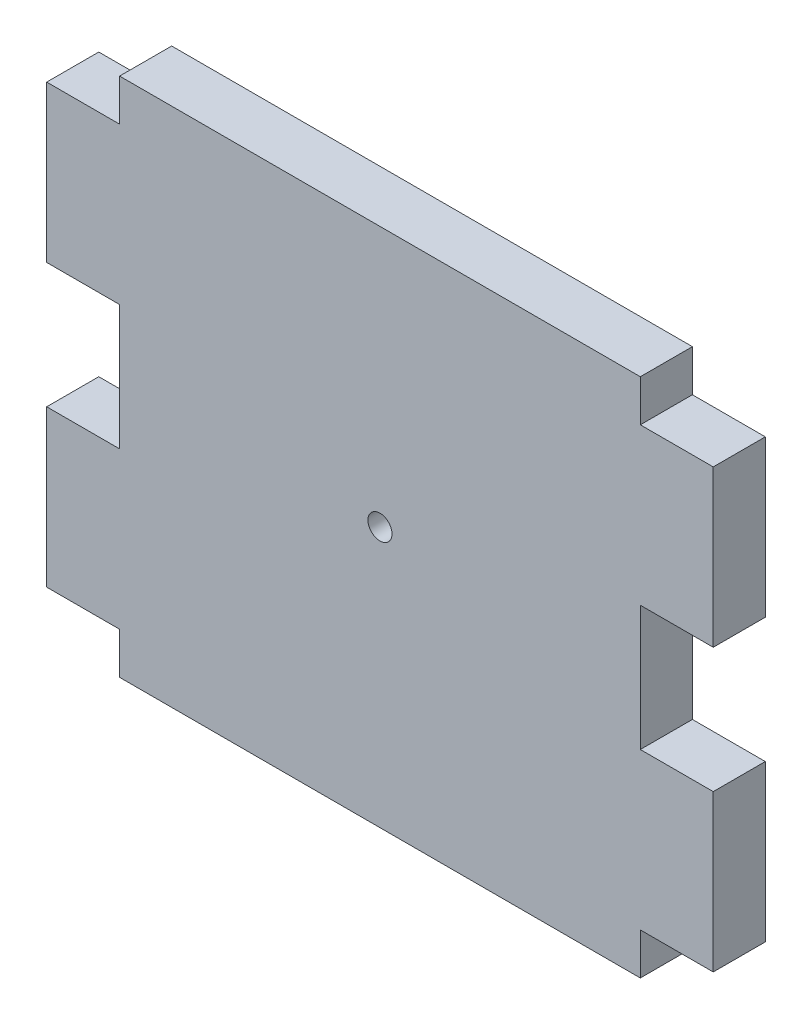
SolidWorks part; units mm, degrees
ref_plane "Front Plane" through (0, 0, 0) normal (0, 0, 1) x (1, 0, 0)
ref_plane "Top Plane" through (0, 0, 0) normal (0, 1, 0) x (1, 0, 0)
ref_plane "Right Plane" through (0, 0, 0) normal (1, 0, 0) x (0, 0, -1)
sketch "Sketch1" plane through (0, 0, 0) normal (0, 0, 1) x (1, 0, 0)
  line L0 (0, 0) -> (50, 0)
  line L2 (50, -50) -> (0, -50)
  line L4 (0, -4) -> (0, 0)
  line L5 (0, -4) -> (-7, -4)
  line L6 (-7, -4) -> (-7, -19)
  line L7 (-7, -19) -> (0, -19)
  line L8 (0, -50) -> (0, -46)
  line L20 (50, 0) -> (50, -4)
  line L21 (50, -19) -> (50, -31)
  line L22 (50, -46) -> (50, -50)
  line L23 (50, -4) -> (57, -4)
  line L24 (57, -4) -> (57, -19)
  line L25 (57, -19) -> (50, -19)
  line L26 (50, -46) -> (57, -46)
  line L27 (57, -46) -> (57, -31)
  line L28 (57, -31) -> (50, -31)
  line L29 (-7, -31) -> (0, -31)
  line L30 (0, -46) -> (-7, -46)
  line L31 (-7, -46) -> (-7, -31)
  line L32 (0, -31) -> (0, -19)
  dimension "D1" = 50
  dimension "D2" = 50
  dimension "D4" = 15
  dimension "D5" = 7
extrude "Boss-Extrude1" add sketch "Sketch1" along normal blind 5
sketch "Sketch2" plane through (0, 0, 5) normal (0, 0, 1) x (1, 0, 0)
  line L0 (25, 0) -> (25, -50) construction
  line L1 (50, 0) -> (0, 0) construction
  line L2 (0, -50) -> (50, -50) construction
  circle A0 centre (25, -25) radius 1.1553
extrude "Cut-Extrude1" cut sketch "Sketch2" against normal blind 10
